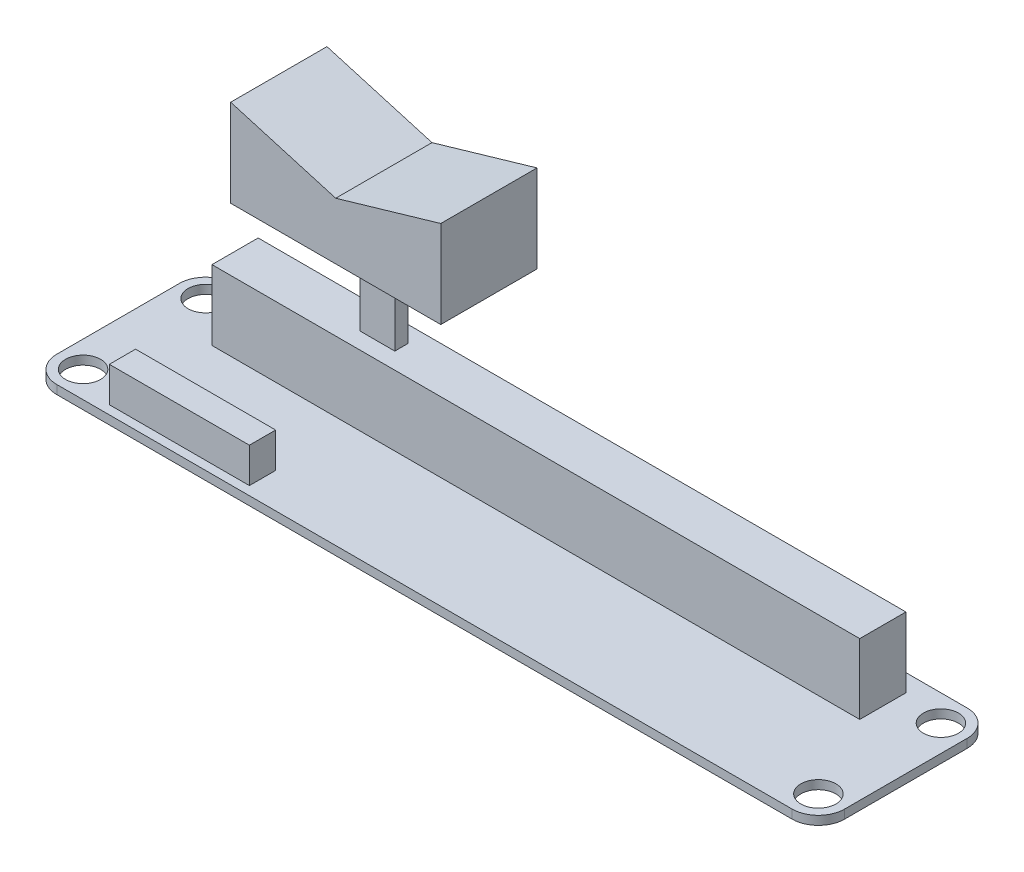
SolidWorks part; units mm, degrees
ref_plane "Front Plane" through (0, 0, 0) normal (0, 0, 1) x (1, 0, 0)
ref_plane "Top Plane" through (0, 0, 0) normal (0, 1, 0) x (1, 0, 0)
ref_plane "Right Plane" through (0, 0, 0) normal (1, 0, 0) x (0, 0, -1)
sketch "Sketch1" plane through (0, 0, 0) normal (0, 1, 0) x (1, 0, 0)
  line L1 (0, 0) -> (90, 0)
  line L2 (0, 0) -> (0, 20)
  line L3 (0, 20) -> (90, 20)
  line L4 (90, 0) -> (90, 20)
  dimension "D1" = 90
  dimension "D2" = 20
extrude "Boss-Extrude1" add sketch "Sketch1" along normal blind 1
sketch "Sketch2" plane through (0, 1, 0) normal (0, 1, 0) x (1, 0, 0)
  line L0 (90, 20) -> (0, 20) construction
  line L1 (0, 20) -> (0, 0) construction
  line L2 (45, 20) -> (45, 0) construction
  line L3 (0, 0) -> (90, 0) construction
  line L4 (0, 10) -> (90, 10) construction
  line L5 (90, 0) -> (90, 20) construction
  circle A0 centre (3, 17) radius 2
  circle A1 centre (87, 17) radius 2
  circle A2 centre (87, 3) radius 2
  circle A3 centre (3, 3) radius 2
  dimension "D1" = 4
  dimension "D2" = 3
  dimension "D3" = 3
extrude "Cut-Extrude1" cut sketch "Sketch2" against normal through all
fillet "Fillet1" radius 3 4 edges at (90, 0.5, -20) (90, 0.5, 0) (0, 0.5, 0) (0, 0.5, -20)
sketch "Sketch3" plane through (0, 1, 0) normal (0, 1, 0) x (1, 0, 0)
  line L0 (87, 20) -> (3, 20) construction
  line L1 (8, 18) -> (82, 18)
  line L2 (8, 18) -> (8, 12.7247)
  line L3 (8, 12.7247) -> (82, 12.7247)
  line L4 (82, 18) -> (82, 12.7247)
  line L5 (90, 3) -> (90, 17) construction
  line L6 (0, 17) -> (0, 3) construction
  point P8 (90, 10)
  dimension "D1" = 2
  dimension "D2" = 8
  dimension "D3" = 8
extrude "Boss-Extrude2" add sketch "Sketch3" along normal blind 8
sketch "Sketch4" plane through (0, 1, 0) normal (0, 1, 0) x (1, 0, 0)
  line L0 (0, 17) -> (0, 3) construction
  line L1 (8, 4) -> (24, 4)
  line L2 (8, 4) -> (8, 1)
  line L3 (8, 1) -> (24, 1)
  line L4 (24, 4) -> (24, 1)
  line L5 (3, 0) -> (87, 0) construction
  dimension "D1" = 16
  dimension "D2" = 3
  dimension "D3" = 8
  dimension "D4" = 1
extrude "Boss-Extrude3" add sketch "Sketch4" along normal blind 4
sketch "Sketch5" plane through (0, 9, 0) normal (0, 1, 0) x (1, 0, 0)
  line L0 (8, 18) -> (8, 12.7247) construction
  line L1 (23, 16.1123) -> (27, 16.1123)
  line L2 (23, 16.1123) -> (23, 14.6123)
  line L3 (23, 14.6123) -> (27, 14.6123)
  line L4 (27, 16.1123) -> (27, 14.6123)
  line L5 (8, 18) -> (8, 12.7247) construction
  point P6 (8, 15.3623)
  point P7 (23, 15.3623)
  dimension "D1" = 4
  dimension "D2" = 1.5
  dimension "D3" = 15
extrude "Boss-Extrude4" add sketch "Sketch5" along normal blind 10
sketch "Sketch6" plane through (0, 19, 0) normal (0, 1, 0) x (1, 0, 0)
  line L0 (27, 14.6123) -> (27, 16.1123) construction
  line L1 (13, 20.8623) -> (37, 20.8623)
  line L2 (13, 20.8623) -> (13, 9.8623)
  line L3 (13, 9.8623) -> (37, 9.8623)
  line L4 (37, 20.8623) -> (37, 9.8623)
  line L6 (27, 16.1123) -> (23, 16.1123) construction
  point P4 (27, 15.3623)
  point P7 (13, 15.3623)
  point P8 (25, 9.8623)
  point P13 (25, 16.1123)
  dimension "D1" = 24
  dimension "D2" = 11
extrude "Boss-Extrude5" add sketch "Sketch6" along normal blind 10
sketch "Sketch7" plane through (0, 0, -9.8623) normal (0, 0, 1) x (1, 0, 0)
  line L0 (37, 29) -> (25, 25.5)
  line L1 (25, 25.5) -> (13, 29)
  line L2 (13, 29) -> (37, 29)
  point P3 (25, 29)
  point P6 (0, 0)
  dimension "D1" = 3.5
extrude "Cut-Extrude2" cut sketch "Sketch7" against normal through all
